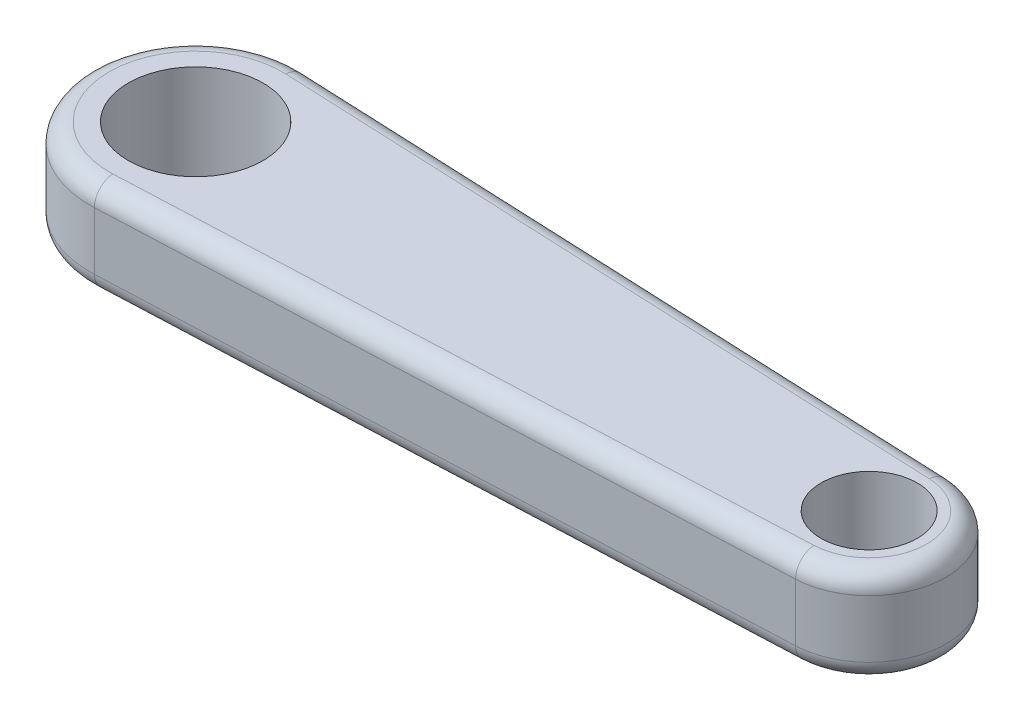
SolidWorks part; units mm, degrees
material "1060-H12"
ref_plane "Alzado" through (0, 0, 0) normal (0, 0, 1) x (1, 0, 0)
ref_plane "Planta" through (0, 0, 0) normal (0, 1, 0) x (1, 0, 0)
ref_plane "Vista lateral" through (0, 0, 0) normal (1, 0, 0) x (0, 0, -1)
sketch "Croquis1" plane through (0, 0, 0) normal (0, 1, 0) x (1, 0, 0)
  line L0 (-147.6429, 54.9495) -> (201.7143, 39.9632)
  line L3 (0, 0) -> (0, 55) construction
  line L4 (-150, 0) -> (207.6415, 0) construction
  line L5 (-147.6429, -54.9495) -> (201.7143, -39.9632)
  circle A2 centre (-150, 0) radius 35
  arc A4 (201.7143, -39.9632) -> (201.7143, 39.9632) centre (200, 0) ccw
  arc A5 (-147.6429, 54.9495) -> (-147.6429, -54.9495) centre (-150, 0) ccw
  circle A6 centre (200, 0) radius 25
  point P0 (129.7759, 0)
  dimension "D3" = 70
  dimension "D4" = 80
  dimension "D1" = 110
  dimension "D2" = 50
  dimension "D5" = 350
  dimension "D6" = 150
extrude "Saliente-Extruir1" add sketch "Croquis1" along normal blind 50
fillet "Redondeo1" radius 10 8 edges at (27.0357, 0, -47.4564) (240, 0, 0) (27.0357, 0, 47.4564) (240, 50, 0) (27.0357, 50, 47.4564) (-205, 50, 0) (-205, 0, 0) (27.0357, 50, -47.4564)
